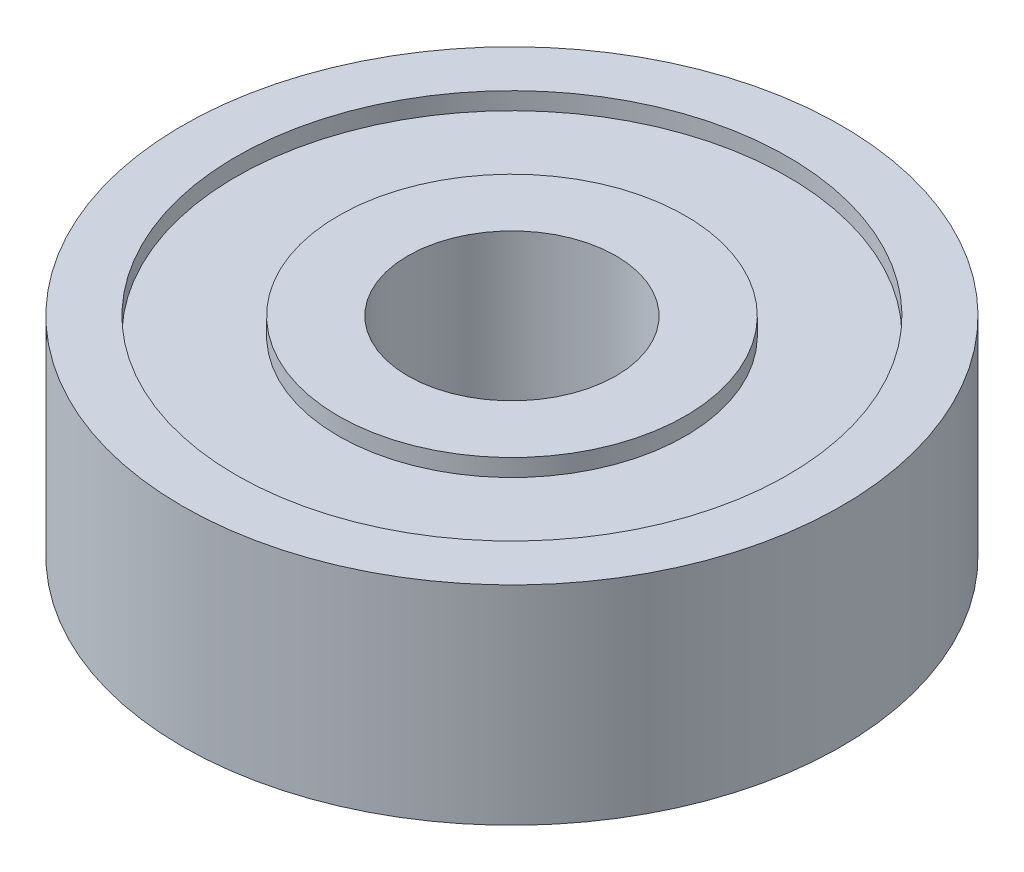
SolidWorks part; units mm, degrees
ref_plane "Front Plane" through (0, 0, 0) normal (0, 0, 1) x (1, 0, 0)
ref_plane "Top Plane" through (0, 0, 0) normal (0, 1, 0) x (1, 0, 0)
ref_plane "Right Plane" through (0, 0, 0) normal (1, 0, 0) x (0, 0, -1)
sketch "Sketch1" plane through (0, 0, 0) normal (0, 1, 0) x (1, 0, 0)
  circle A0 centre (0, 0) radius 3
  circle A1 centre (0, 0) radius 9.5
extrude "Boss-Extrude1" add sketch "Sketch1" along normal blind 6
sketch "Sketch2" plane through (0, 6, 0) normal (0, 1, 0) x (1, 0, 0)
  circle A0 centre (0, 0) radius 5.0015
  circle A1 centre (0, 0) radius 7.95
extrude "Cut-Extrude1" cut sketch "Sketch2" against normal blind 0.5
sketch "Sketch3" plane through (0, 0, 0) normal (0, -1, 0) x (1, 0, 0)
  circle A0 centre (0, 0) radius 5.0025
  circle A1 centre (0, 0) radius 7.95
extrude "Cut-Extrude2" cut sketch "Sketch3" against normal blind 0.5
